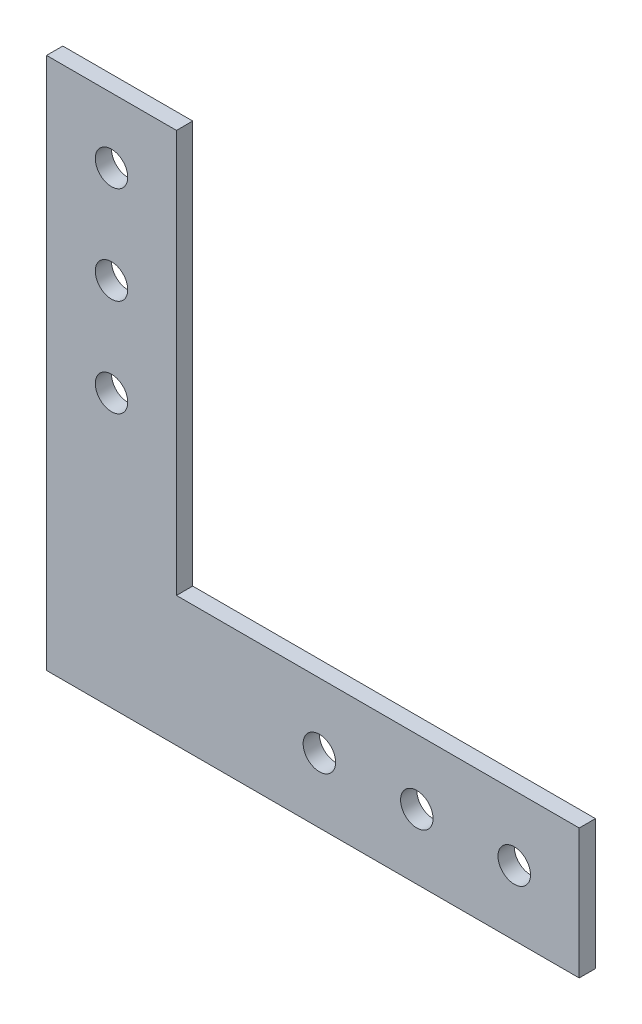
SolidWorks part; units mm, degrees
ref_plane "Front Plane" through (0, 0, 0) normal (0, 0, 1) x (1, 0, 0)
ref_plane "Top Plane" through (0, 0, 0) normal (0, 1, 0) x (1, 0, 0)
ref_plane "Right Plane" through (0, 0, 0) normal (1, 0, 0) x (0, 0, -1)
sketch "Sketch1" plane through (0, 0, 0) normal (0, 0, 1) x (1, 0, 0)
  line L1 (0, 0) -> (25.4, 0)
  line L2 (0, 0) -> (0, 104.14)
  line L3 (0, 104.14) -> (25.4, 104.14)
  line L4 (25.4, 25.4) -> (25.4, 104.14)
  line L5 (0, 0) -> (104.14, 0)
  line L6 (0, 0) -> (0, 25.4)
  line L7 (25.4, 25.4) -> (104.14, 25.4)
  line L8 (104.14, 0) -> (104.14, 25.4)
  dimension "D1" = 25.4
  dimension "D2" = 25.4
  dimension "D3" = 104.14
  dimension "D4" = 104.14
extrude "Boss-Extrude1" add sketch "Sketch1" along normal blind 3.175 contours L5 L8 L7 L4 L3 L2 L1
sketch "Sketch2" plane through (0, 0, 3.175) normal (0, 0, 1) x (1, 0, 0)
  line L0 (0, 0) -> (104.14, 0) construction
  line L1 (0, 0) -> (0, 104.14) construction
  line L2 (25.4, 25.4) -> (104.14, 25.4) construction
  circle A0 centre (53.34, 12.7) radius 3.175
  circle A1 centre (72.39, 12.7) radius 3.175
  circle A2 centre (12.7, 53.34) radius 3.175
  circle A3 centre (12.7, 72.39) radius 3.175
  circle A4 centre (12.7, 91.44) radius 3.175
  circle A5 centre (91.44, 12.7) radius 3.175
  dimension "D5" = 6.35
  dimension "D6" = 6.35
  dimension "D7" = 6.35
  dimension "D8" = 6.35
  dimension "D9" = 6.35
  dimension "D10" = 6.35
  dimension "D1" = 53.34
  dimension "D2" = 53.34
  dimension "D3" = 19.05
  dimension "D4" = 19.05
  dimension "D11" = 19.05
  dimension "D12" = 19.05
  dimension "D13" = 12.7
  dimension "D14" = 12.7
  dimension "D15" = 12.7
  dimension "D16" = 12.7
  dimension "D17" = 12.7
  dimension "D18" = 12.7
extrude "Cut-Extrude1" cut sketch "Sketch2" against normal through all
